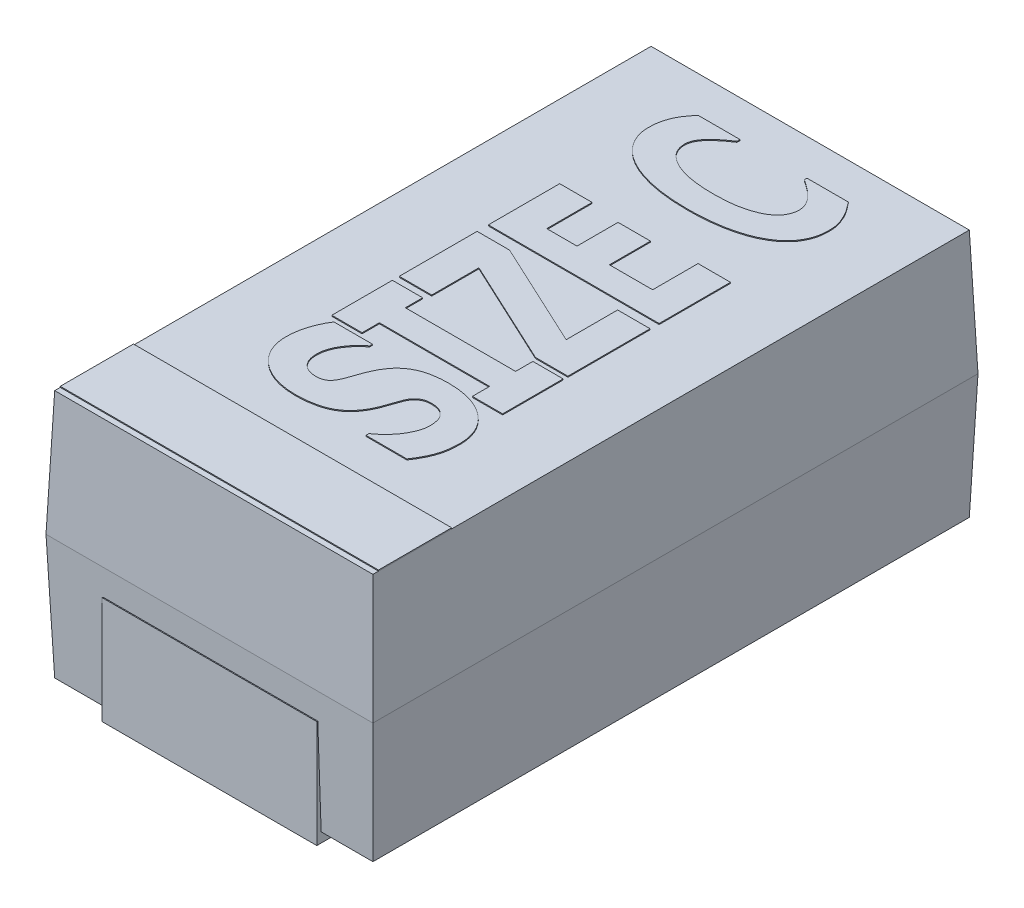
SolidWorks part; units mm, degrees
ref_plane "Front Plane" through (0, 0, 0) normal (0, 0, 1) x (1, 0, 0)
ref_plane "Top Plane" through (0, 0, 0) normal (0, 1, 0) x (1, 0, 0)
ref_plane "Right Plane" through (0, 0, 0) normal (1, 0, 0) x (0, 0, -1)
sketch "Sketch1" plane through (0, 0, 0) normal (0, 1, 0) x (1, 0, 0)
  line L1 (-1.675, 3.1) -> (1.675, 3.1)
  line L2 (-1.675, 3.1) -> (-1.675, -3.1)
  line L3 (-1.675, -3.1) -> (1.675, -3.1)
  line L4 (1.675, 3.1) -> (1.675, -3.1)
  line L5 (-1.675, 3.1) -> (1.675, -3.1) construction
  line L6 (-1.675, -3.1) -> (1.675, 3.1) construction
  point P0 (0, 0)
  dimension "D1" = 3.35
  dimension "D2" = 6.2
extrude "Boss-Extrude1" add sketch "Sketch1" along normal mid plane 2.55 draft 2
sketch "Sketch2" plane through (0, -1.275, 0) normal (0, -1, 0) x (1, 0, 0)
  line L0 (0, 0) -> (3.8147, 0) construction
  line L1 (-1.1, 3.1) -> (1.1, 3.1)
  line L2 (-1.1, 3.1) -> (-1.1, 1.75)
  line L3 (-1.1, 1.75) -> (1.1, 1.75)
  line L4 (1.1, 3.1) -> (1.1, 1.75)
  line L5 (-1.1, 3.1) -> (1.1, 1.75) construction
  line L6 (-1.1, 1.75) -> (1.1, 3.1) construction
  line L7 (-1.1, -1.75) -> (1.1, -1.75)
  line L8 (1.1, -3.1) -> (1.1, -1.75)
  line L9 (-1.1, -3.1) -> (1.1, -3.1)
  line L10 (-1.1, -3.1) -> (-1.1, -1.75)
  point P0 (0, 2.425)
  dimension "D1" = 2.2
  dimension "D2" = 1.35
  dimension "D3" = 6.2
extrude "Boss-Extrude2" add sketch "Sketch2" along normal blind 0.1 and the other way blind 1
sketch "Sketch3" plane through (0, 1.275, 0) normal (0, 1, 0) x (1, 0, 0)
  line L0 (-1.6305, -2.6235) -> (1.6305, -2.6235)
  line L1 (-1.6305, 3.0555) -> (-1.6305, -3.0555) construction
  line L2 (1.6305, -3.0555) -> (1.6305, 3.0555) construction
extrude "Extrude-Thin1" add sketch "Sketch3" along normal blind 0.01 thin thin type mid plane wall 0.75
sketch "Sketch4" plane through (0, 1.275, 0) normal (0, 1, 0) x (1, 0, 0)
  line L0 (0.8805, -2.2485) -> (0.8805, 3.0555) construction
  line L1 (1.6305, 3.0555) -> (-1.6305, 3.0555) construction
  line L2 (1.6305, -2.2485) -> (1.6305, 3.0555) construction
  line L3 (-1.6305, -2.2485) -> (1.6305, -2.2485) construction
  text T0 "SIZE C" font "Verdana" height 1.75
  point P6 (1.3805, -2.2485)
  dimension "D1" = 0.75
extrude "Boss-Extrude3" add sketch "Sketch4" along normal blind 0.01
